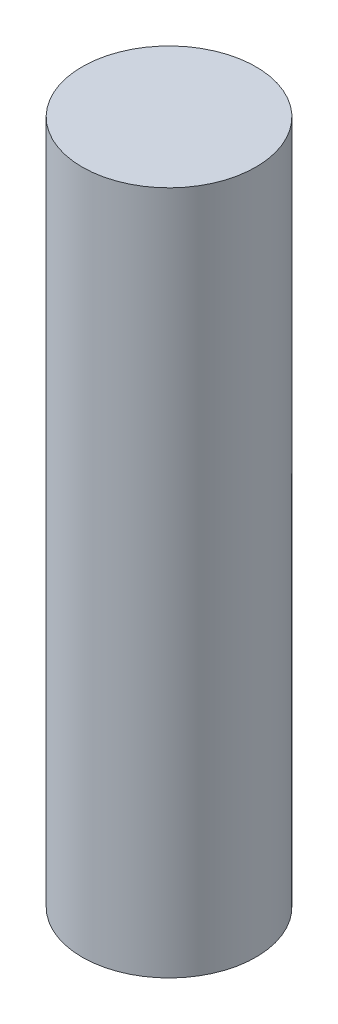
SolidWorks part; units mm, degrees
ref_plane "Front Plane" through (0, 0, 0) normal (0, 0, 1) x (1, 0, 0)
ref_plane "Top Plane" through (0, 0, 0) normal (0, 1, 0) x (1, 0, 0)
ref_plane "Right Plane" through (0, 0, 0) normal (1, 0, 0) x (0, 0, -1)
sketch "Sketch1" plane through (0, 0, 0) normal (0, 1, 0) x (1, 0, 0)
  circle A0 centre (-72.8312, 7.0125) radius 25.4
extrude "Boss-Extrude1" add sketch "Sketch1" along normal blind 200
